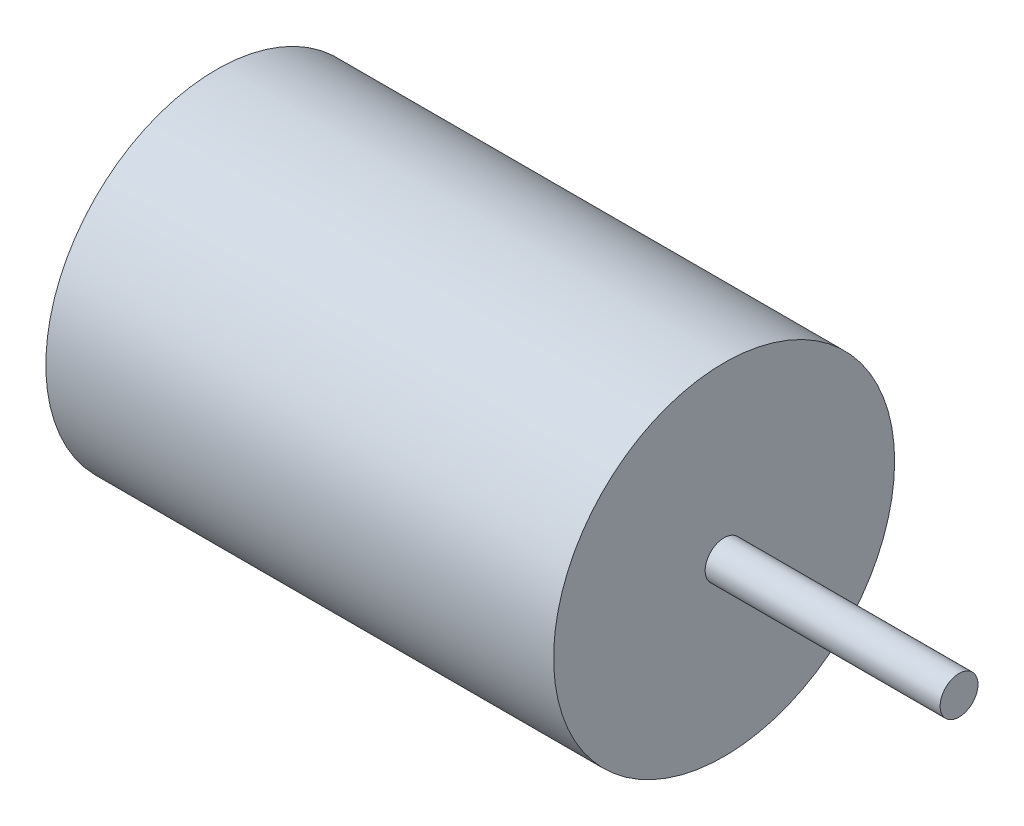
SolidWorks part; units mm, degrees
ref_plane "Front Plane" through (0, 0, 0) normal (0, 0, 1) x (1, 0, 0)
ref_plane "Top Plane" through (0, 0, 0) normal (0, 1, 0) x (1, 0, 0)
ref_plane "Right Plane" through (0, 0, 0) normal (1, 0, 0) x (0, 0, -1)
sketch "Sketch2" plane through (0, 0, 0) normal (1, 0, 0) x (0, 0, -1)
  circle A0 centre (0, 0) radius 22.5
  dimension "D1" = 45
extrude "Boss-Extrude1" add sketch "Sketch2" along normal blind 67 contours A0
sketch "Sketch3" plane through (67, 0, 0) normal (1, 0, 0) x (0, 0, -1)
  circle A0 centre (0, 0) radius 2.5
  dimension "D1" = 5
extrude "Boss-Extrude2" add sketch "Sketch3" along normal blind 31
